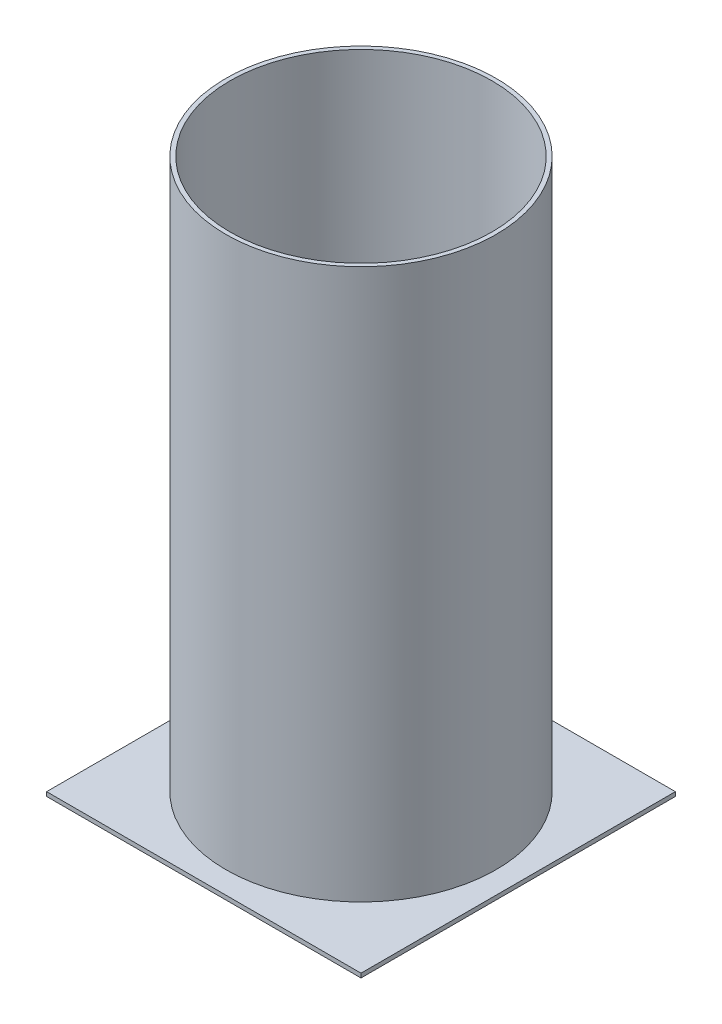
SolidWorks part; units mm, degrees
ref_plane "Front Plane" through (0, 0, 0) normal (0, 0, 1) x (1, 0, 0)
ref_plane "Top Plane" through (0, 0, 0) normal (0, 1, 0) x (1, 0, 0)
ref_plane "Right Plane" through (0, 0, 0) normal (1, 0, 0) x (0, 0, -1)
sketch "Sketch1" plane through (0, 0, 0) normal (0, 1, 0) x (1, 0, 0)
  line L0 (0, 0) -> (300, 0)
  line L1 (300, 0) -> (300, 300)
  line L2 (300, 300) -> (0, 300)
  line L3 (0, 300) -> (0, 0)
  dimension "D1" = 300
  dimension "D2" = 300
extrude "Boss-Extrude2" add sketch "Sketch1" along normal blind 4 contours L3 L0 L1 L2
sketch "Sketch2" plane through (0, 4, 0) normal (0, 1, 0) x (1, 0, 0)
  line L0 (300, 300) -> (0, 300) construction
  line L1 (0, 300) -> (0, 0) construction
  circle A0 centre (150, 150) radius 129
  circle A1 centre (150, 150) radius 125
  point P3 (0, 0)
  point P4 (0, 0)
  dimension "D1" = 250
  dimension "258" = 258
  dimension "D2" = 150
  dimension "D3" = 150
extrude "Boss-Extrude3" add sketch "Sketch2" along normal blind 525 contours A0
